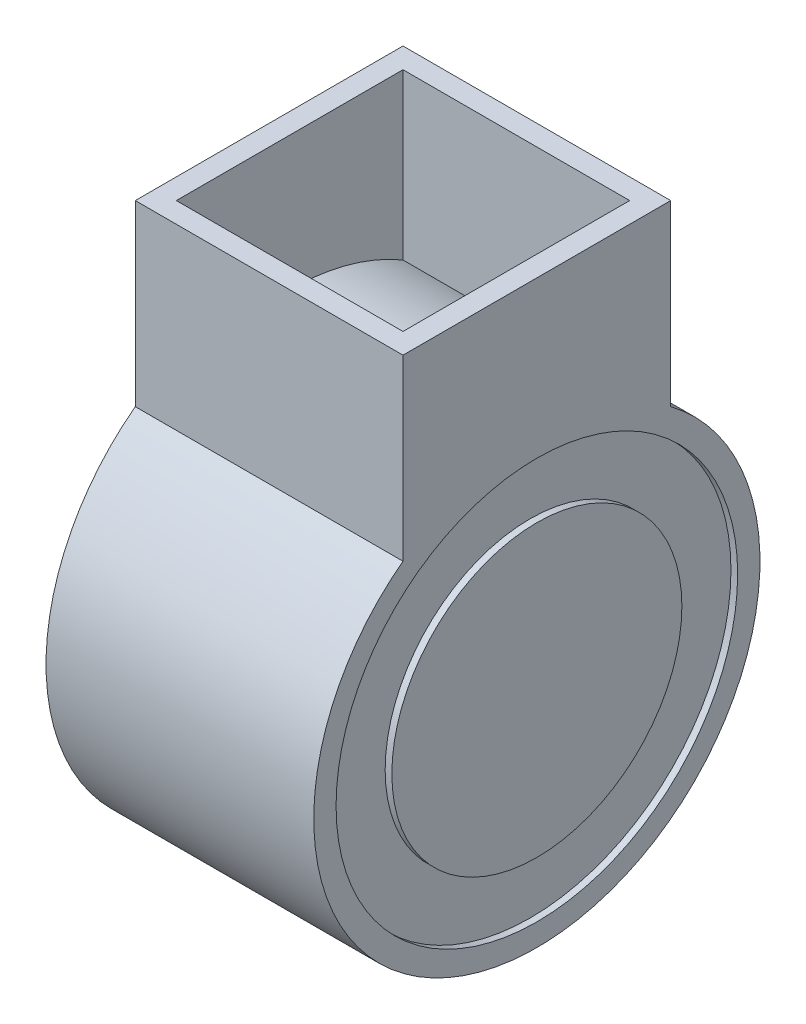
SolidWorks part; units mm, degrees
material "ABS"
ref_plane "Alzado" through (0, 0, 0) normal (0, 0, 1) x (1, 0, 0)
ref_plane "Planta" through (0, 0, 0) normal (0, 1, 0) x (1, 0, 0)
ref_plane "Vista lateral" through (0, 0, 0) normal (1, 0, 0) x (0, 0, -1)
sketch "Croquis1" plane through (0, 0, 0) normal (1, 0, 0) x (0, 0, -1)
  circle A0 centre (0, 0) radius 50
  dimension "D1" = 100
extrude "Saliente-Extruir1" add sketch "Croquis1" along normal mid plane 60
ref_plane "Plano1" through (0, 80, 0) normal (0, 1, 0) x (1, 0, 0)
sketch "Croquis3" plane through (0, 80, 0) normal (0, 1, 0) x (1, 0, 0)
  line L1 (-30, -30) -> (30, -30)
  line L2 (-30, -30) -> (-30, 30)
  line L3 (-30, 30) -> (30, 30)
  line L4 (30, -30) -> (30, 30)
  line L5 (-30, -30) -> (30, 30) construction
  line L6 (-30, 30) -> (30, -30) construction
  line L7 (-25.4, -25.4) -> (25.4, -25.4)
  line L8 (-25.4, -25.4) -> (-25.4, 25.4)
  line L9 (-25.4, 25.4) -> (25.4, 25.4)
  line L10 (25.4, -25.4) -> (25.4, 25.4)
  line L11 (-25.4, -25.4) -> (25.4, 25.4) construction
  line L12 (-25.4, 25.4) -> (25.4, -25.4) construction
  point P0 (0, 0)
  point P6 (0, 0)
  dimension "D1" = 60
  dimension "D2" = 50.8
extrude "Saliente-Extruir2" add sketch "Croquis3" against normal up to next
sketch "Croquis4" plane through (30, 0, 0) normal (1, 0, 0) x (0, 0, -1)
  circle A0 centre (0, 0) radius 45
  circle A1 centre (0, 0) radius 32.5
  dimension "D1" = 90
  dimension "D2" = 65
extrude "Cortar-Extruir1" cut sketch "Croquis4" against normal blind 1.5
mirror "Simetría1" about plane through (0, 0, 0) normal (1, 0, 0) of "Cortar-Extruir1"
